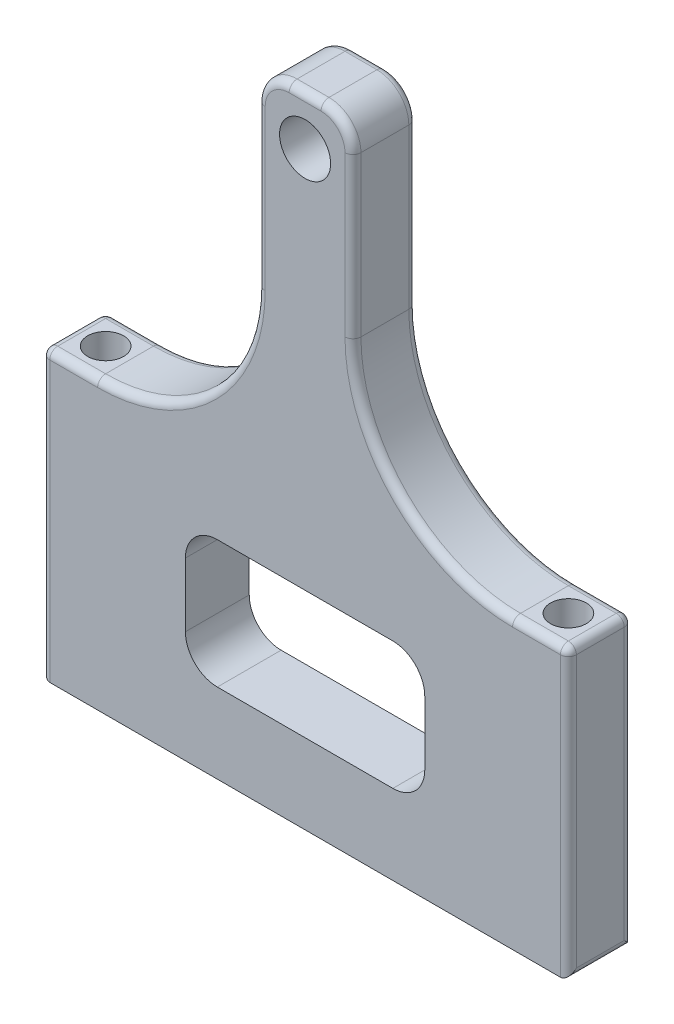
SolidWorks part; units mm, degrees
ref_plane "Front Plane" through (0, 0, 0) normal (0, 0, 1) x (1, 0, 0)
ref_plane "Top Plane" through (0, 0, 0) normal (0, 1, 0) x (1, 0, 0)
ref_plane "Right Plane" through (0, 0, 0) normal (1, 0, 0) x (0, 0, -1)
sketch "Sketch1" plane through (0, 0, 0) normal (0, 0, 1) x (1, 0, 0)
  line L0 (3.81, 0) -> (-3.81, 0) construction
  line L1 (16.5, -9) -> (-16.5, -9)
  line L2 (16.5, -9) -> (16.5, 9)
  line L3 (16.5, 9) -> (3, 9)
  line L4 (-16.5, -9) -> (-16.5, 9)
  line L5 (16.5, -9) -> (-16.5, 9) construction
  line L6 (16.5, 9) -> (-16.5, -9) construction
  line L7 (-3, 9) -> (-3, 31)
  line L8 (-3, 31) -> (3, 31)
  line L9 (3, 31) -> (3, 9)
  line L10 (-16.5, 9) -> (-3, 9)
  line L14 (-5.2, 31.75) -> (5.2, 31.75) construction
  line L15 (-5.2, 31.75) -> (-5.2, -1.27) construction
  line L16 (-5.2, -1.27) -> (5.2, -1.27) construction
  line L17 (5.2, 31.75) -> (5.2, -1.27) construction
  line L18 (-5.2, 31.75) -> (5.2, -1.27) construction
  line L19 (-5.2, -1.27) -> (5.2, 31.75) construction
  line L20 (-7.5, 4) -> (7.5, 4)
  line L21 (-7.5, 4) -> (-7.5, -4)
  line L22 (-7.5, -4) -> (7.5, -4)
  line L23 (7.5, 4) -> (7.5, -4)
  circle A0 centre (-3.81, 0) radius 0.5 construction
  circle A1 centre (3.81, 0) radius 0.5 construction
  circle A2 centre (-1.27, 0) radius 0.5 construction
  circle A3 centre (1.27, 0) radius 0.5 construction
  circle A4 centre (0, 27.95) radius 1.6
  point P0 (0, 0)
  point P8 (0, 0)
  point P17 (0, 31)
  point P26 (7.5, 0)
  point P27 (0, 4)
  point P29 (0, 15.24)
  point P35 (0, -1.27)
  dimension "D4" = 1
  dimension "D9" = 3.2
  dimension "D1" = 18
  dimension "D2" = 33
  dimension "D3" = 2.54
  dimension "D5" = 2.54
  dimension "D6" = 2.54
  dimension "D7" = 31
  dimension "D8" = 6
  dimension "D10" = 10.4
  dimension "D11" = 33.02
  dimension "D12" = 1.27
  dimension "D13" = 3.8
  dimension "D14" = 15
  dimension "D15" = 8
extrude "Boss-Extrude1" add sketch "Sketch1" along normal mid plane 4 contours L3 L4 L1 L2
sketch "Sketch2" plane through (0, 9, 0) normal (0, 1, 0) x (1, 0, 0)
  line L0 (-14.5, 0) -> (14.5, 0) construction
  circle A0 centre (-14.5, 0) radius 1.125
  circle A1 centre (14.5, 0) radius 1.125
  point P4 (0, 0)
  dimension "D2" = 2.25
  dimension "D1" = 29
extrude "Cut-Extrude1" cut sketch "Sketch2" against normal through all
fillet "Fillet2" radius 10 2 edges at (-3, 9, 0) (3, 9, 0)
fillet "Fillet3" radius 2 2 edges at (3, 31, 0) (-3, 31, 0)
fillet "Fillet6" radius 2 4 edges at (7.5, -4, 0) (7.5, 4, 0) (-7.5, -4, 0) (-7.5, 4, 0)
fillet "Fillet5" radius 0.5 26 edges at (-14.75, 9, -2) (14.75, 9, -2) (5.9289, 11.9289, -2) (3, 24, -2) (2.4142, 30.4142, -2) (0, 31, -2) (-2.4142, 30.4142, -2) (-3, 24, -2) (14.75, 9, 2) (5.9289, 11.9289, 2) (3, 24, 2) (2.4142, 30.4142, 2) (0, 31, 2) (-2.4142, 30.4142, 2) (16.5, -9, 0) (16.5, 0, 2) (16.5, 9, 0) (16.5, 0, -2) (-16.5, 9, 0) (-16.5, 0, 2) (-16.5, -9, 0) (-16.5, 0, -2) (-5.9289, 11.9289, -2) (-5.9289, 11.9289, 2) (-3, 24, 2) (-14.75, 9, 2)
